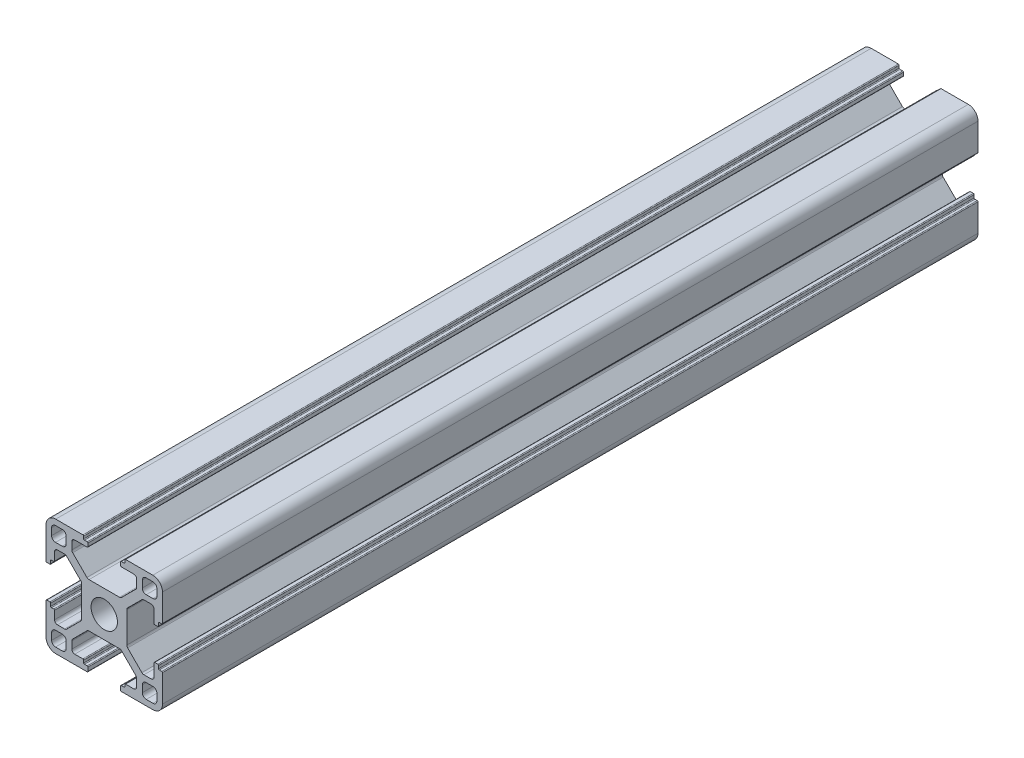
SolidWorks part; units mm, degrees
material "6063-T5"
ref_plane "Front Plane" through (0, 0, 0) normal (0, 0, 1) x (1, 0, 0)
ref_plane "Top Plane" through (0, 0, 0) normal (0, 1, 0) x (1, 0, 0)
ref_plane "Right Plane" through (0, 0, 0) normal (1, 0, 0) x (0, 0, -1)
sketch "Sketch1" plane through (0, 0, 0) normal (0, 0, 1) x (1, 0, 0)
  line L0 (0, 2.5) -> (0, 10.6)
  line L1 (2.5, 30) -> (9.5, 30)
  line L2 (30, 27.5) -> (30, 20.5)
  line L3 (27.5, 0) -> (19.4, 0)
  line L4 (19.464, 9.1128) -> (23.1303, 5.4465)
  line L5 (21.0197, 10.536) -> (24.686, 6.8697)
  line L6 (10.536, 21.0197) -> (6.8697, 24.686)
  line L7 (8.9803, 19.464) -> (5.314, 23.1303)
  line L8 (11.0663, 20.8) -> (18.9337, 20.8)
  line L9 (20.8, 18.9337) -> (20.8, 11.0663)
  line L10 (18.9337, 9.3324) -> (11.0663, 9.3324)
  line L11 (9.2, 11.0663) -> (9.2, 18.9337)
  line L12 (0, 19.4) -> (0, 27.5)
  line L13 (30, 9.5) -> (30, 2.5)
  line L14 (19.4, 27.8) -> (22.6, 27.8)
  line L15 (10.6, 27.8) -> (7.4, 27.8)
  line L16 (10.6, 0) -> (2.5, 0)
  line L17 (2.2, 20.5) -> (2.2, 22.6)
  line L18 (2.2, 9.5) -> (2.2, 7.4)
  line L19 (9.5, 2.3324) -> (7.4, 2.3324)
  line L20 (19.464, 21.0197) -> (23.1303, 24.686)
  line L21 (21.0197, 19.464) -> (24.686, 23.1303)
  line L22 (8.9803, 10.536) -> (5.314, 6.8697)
  line L23 (10.536, 9.1128) -> (6.8697, 5.4465)
  line L24 (10.8, 28.8) -> (10.8, 28)
  line L25 (19.2, 28.8) -> (19.2, 28)
  line L26 (0.2, 19.2) -> (1, 19.2)
  line L27 (0.2, 10.8) -> (1, 10.8)
  line L28 (28.8, 19.2) -> (28, 19.2)
  line L29 (28.8, 10.8) -> (28, 10.8)
  line L30 (10.8, 0.2) -> (10.8, 1.1324)
  line L31 (19.2, 0.2) -> (19.2, 1.1324)
  line L32 (20.5, 30) -> (27.5, 30)
  line L33 (27.8, 19.4) -> (27.8, 22.6)
  line L34 (27.8, 10.6) -> (27.8, 7.4)
  line L35 (20.5, 2.2) -> (22.6, 2.2)
  line L36 (6.65, 27.05) -> (6.65, 25.2163)
  line L37 (23.35, 27.05) -> (23.35, 25.2163)
  line L38 (2.95, 23.35) -> (4.7837, 23.35)
  line L39 (27.05, 23.35) -> (25.2163, 23.35)
  line L40 (2.95, 6.65) -> (4.7837, 6.65)
  line L41 (6.65, 3.0824) -> (6.65, 4.9161)
  line L42 (23.35, 2.95) -> (23.35, 4.9161)
  line L43 (27.05, 6.65) -> (25.2163, 6.65)
  line L44 (29, 10.6) -> (29, 9.9)
  line L45 (29.8, 20.3) -> (29.2, 20.3)
  line L46 (29, 20.1) -> (29, 19.4)
  line L47 (29.2, 9.7) -> (29.8, 9.7)
  line L48 (19.4, 29) -> (20.1, 29)
  line L49 (9.7, 29.8) -> (9.7, 29.2)
  line L50 (9.9, 29) -> (10.6, 29)
  line L51 (20.3, 29.2) -> (20.3, 29.8)
  line L52 (9.7, 2.1324) -> (9.7, 1.5324)
  line L53 (9.9, 1.3324) -> (10.6, 1.3324)
  line L54 (19.4, 1.3324) -> (20.1, 1.3324)
  line L55 (20.3, 1.5324) -> (20.3, 2)
  line L56 (2, 20.3) -> (1.4, 20.3)
  line L57 (1.2, 20.1) -> (1.2, 19.4)
  line L58 (1.2, 10.6) -> (1.2, 9.9)
  line L59 (1.4, 9.7) -> (2, 9.7)
  line L60 (27.55, 1.45) -> (25.8, 1.45)
  line L61 (24.8, 2.45) -> (24.8, 4.2)
  line L62 (25.8, 5.2) -> (27.55, 5.2)
  line L63 (28.55, 4.2) -> (28.55, 2.45)
  line L64 (24.8, 25.8) -> (24.8, 27.55)
  line L65 (25.8, 28.55) -> (27.55, 28.55)
  line L66 (28.55, 27.55) -> (28.55, 25.8)
  line L67 (27.55, 24.8) -> (25.8, 24.8)
  line L68 (2.45, 28.55) -> (4.2, 28.55)
  line L69 (5.2, 27.55) -> (5.2, 25.8)
  line L70 (1.45, 2.45) -> (1.45, 4.2)
  line L71 (2.45, 5.2) -> (4.2, 5.2)
  line L72 (5.2, 4.2) -> (5.2, 2.45)
  line L73 (4.2, 1.45) -> (2.45, 1.45)
  line L74 (4.2, 24.8) -> (2.45, 24.8)
  line L75 (1.45, 25.8) -> (1.45, 27.55)
  circle A0 centre (15, 15) radius 3.4
  arc A1 (25.8, 1.45) -> (24.8, 2.45) centre (25.8, 2.45) cw
  arc A2 (27.55, 1.45) -> (28.55, 2.45) centre (27.55, 2.45) ccw
  arc A3 (27.55, 5.2) -> (28.55, 4.2) centre (27.55, 4.2) cw
  arc A4 (24.8, 4.2) -> (25.8, 5.2) centre (25.8, 4.2) cw
  arc A5 (1.45, 2.45) -> (2.45, 1.45) centre (2.45, 2.45) ccw
  arc A6 (5.2, 2.45) -> (4.2, 1.45) centre (4.2, 2.45) cw
  arc A7 (4.2, 5.2) -> (5.2, 4.2) centre (4.2, 4.2) cw
  arc A8 (1.45, 4.2) -> (2.45, 5.2) centre (2.45, 4.2) cw
  arc A9 (24.8, 25.8) -> (25.8, 24.8) centre (25.8, 25.8) ccw
  arc A10 (28.55, 25.8) -> (27.55, 24.8) centre (27.55, 25.8) cw
  arc A11 (27.55, 28.55) -> (28.55, 27.55) centre (27.55, 27.55) cw
  arc A12 (24.8, 27.55) -> (25.8, 28.55) centre (25.8, 27.55) cw
  arc A13 (4.2, 28.55) -> (5.2, 27.55) centre (4.2, 27.55) cw
  arc A14 (5.2, 25.8) -> (4.2, 24.8) centre (4.2, 25.8) cw
  arc A15 (2.45, 24.8) -> (1.45, 25.8) centre (2.45, 25.8) cw
  arc A16 (2.45, 28.55) -> (1.45, 27.55) centre (2.45, 27.55) ccw
  arc A17 (30, 2.5) -> (27.5, 0) centre (27.5, 2.5) cw
  arc A18 (0, 2.5) -> (2.5, 0) centre (2.5, 2.5) ccw
  arc A19 (27.5, 30) -> (30, 27.5) centre (27.5, 27.5) cw
  arc A20 (0, 27.5) -> (2.5, 30) centre (2.5, 27.5) cw
  arc A21 (0, 10.6) -> (0.2, 10.8) centre (0.2, 10.6) cw
  arc A22 (1.2, 10.6) -> (1, 10.8) centre (1, 10.6) ccw
  arc A23 (2, 9.7) -> (2.2, 9.5) centre (2, 9.5) cw
  arc A24 (9.7, 2.1324) -> (9.5, 2.3324) centre (9.5, 2.1324) ccw
  arc A25 (10.6, 1.3324) -> (10.8, 1.1324) centre (10.6, 1.1324) cw
  arc A26 (10.6, 0) -> (10.8, 0.2) centre (10.6, 0.2) ccw
  arc A27 (19.4, 0) -> (19.2, 0.2) centre (19.4, 0.2) cw
  arc A28 (19.4, 1.3324) -> (19.2, 1.1324) centre (19.4, 1.1324) ccw
  arc A29 (20.3, 2) -> (20.5, 2.2) centre (20.5, 2) cw
  arc A30 (28, 10.8) -> (27.8, 10.6) centre (28, 10.6) ccw
  arc A31 (29, 10.6) -> (28.8, 10.8) centre (28.8, 10.6) ccw
  arc A32 (29.8, 9.7) -> (30, 9.5) centre (29.8, 9.5) cw
  arc A33 (28, 19.2) -> (27.8, 19.4) centre (28, 19.4) cw
  arc A34 (29, 19.4) -> (28.8, 19.2) centre (28.8, 19.4) cw
  arc A35 (30, 20.5) -> (29.8, 20.3) centre (29.8, 20.5) cw
  arc A36 (20.3, 29.8) -> (20.5, 30) centre (20.5, 29.8) cw
  arc A37 (19.4, 29) -> (19.2, 28.8) centre (19.4, 28.8) ccw
  arc A38 (19.2, 28) -> (19.4, 27.8) centre (19.4, 28) ccw
  arc A39 (10.8, 28) -> (10.6, 27.8) centre (10.6, 28) cw
  arc A40 (0, 19.4) -> (0.2, 19.2) centre (0.2, 19.4) ccw
  arc A41 (1.2, 19.4) -> (1, 19.2) centre (1, 19.4) cw
  arc A42 (2, 20.3) -> (2.2, 20.5) centre (2, 20.5) ccw
  arc A43 (10.6, 29) -> (10.8, 28.8) centre (10.6, 28.8) cw
  arc A44 (9.5, 30) -> (9.7, 29.8) centre (9.5, 29.8) cw
  arc A45 (1.4, 20.3) -> (1.2, 20.1) centre (1.4, 20.1) ccw
  arc A46 (20.1, 29) -> (20.3, 29.2) centre (20.1, 29.2) ccw
  arc A47 (9.7, 29.2) -> (9.9, 29) centre (9.9, 29.2) ccw
  arc A48 (29.2, 20.3) -> (29, 20.1) centre (29.2, 20.1) ccw
  arc A49 (29, 9.9) -> (29.2, 9.7) centre (29.2, 9.9) ccw
  arc A50 (20.1, 1.3324) -> (20.3, 1.5324) centre (20.1, 1.5324) ccw
  arc A51 (1.2, 9.9) -> (1.4, 9.7) centre (1.4, 9.9) ccw
  arc A52 (9.7, 1.5324) -> (9.9, 1.3324) centre (9.9, 1.5324) ccw
  arc A53 (23.35, 25.2163) -> (23.1303, 24.686) centre (22.6, 25.2163) cw
  arc A54 (25.2163, 23.35) -> (24.686, 23.1303) centre (25.2163, 22.6) ccw
  arc A55 (20.8, 18.9337) -> (21.0197, 19.464) centre (21.55, 18.9337) cw
  arc A56 (18.9337, 20.8) -> (19.464, 21.0197) centre (18.9337, 21.55) ccw
  arc A57 (6.65, 25.2163) -> (6.8697, 24.686) centre (7.4, 25.2163) ccw
  arc A58 (11.0663, 20.8) -> (10.536, 21.0197) centre (11.0663, 21.55) cw
  arc A59 (4.7837, 23.35) -> (5.314, 23.1303) centre (4.7837, 22.6) cw
  arc A60 (9.2, 18.9337) -> (8.9803, 19.464) centre (8.45, 18.9337) ccw
  arc A61 (4.7837, 6.65) -> (5.314, 6.8697) centre (4.7837, 7.4) ccw
  arc A62 (9.2, 11.0663) -> (8.9803, 10.536) centre (8.45, 11.0663) cw
  arc A63 (6.65, 4.9161) -> (6.8697, 5.4465) centre (7.4, 4.9161) cw
  arc A64 (11.0663, 9.3324) -> (10.536, 9.1128) centre (11.0663, 8.5824) ccw
  arc A65 (18.9337, 9.3324) -> (19.464, 9.1128) centre (18.9337, 8.5824) cw
  arc A66 (20.8, 11.0663) -> (21.0197, 10.536) centre (21.55, 11.0663) ccw
  arc A67 (25.2163, 6.65) -> (24.686, 6.8697) centre (25.2163, 7.4) cw
  arc A68 (23.35, 4.9161) -> (23.1303, 5.4465) centre (22.6, 4.9161) ccw
  arc A69 (7.4, 2.3324) -> (6.65, 3.0824) centre (7.4, 3.0824) cw
  arc A70 (22.6, 2.2) -> (23.35, 2.95) centre (22.6, 2.95) ccw
  arc A71 (27.8, 7.4) -> (27.05, 6.65) centre (27.05, 7.4) cw
  arc A72 (27.8, 22.6) -> (27.05, 23.35) centre (27.05, 22.6) ccw
  arc A73 (22.6, 27.8) -> (23.35, 27.05) centre (22.6, 27.05) cw
  arc A74 (2.2, 7.4) -> (2.95, 6.65) centre (2.95, 7.4) ccw
  arc A75 (2.2, 22.6) -> (2.95, 23.35) centre (2.95, 22.6) cw
  arc A76 (7.4, 27.8) -> (6.65, 27.05) centre (7.4, 27.05) ccw
  point P115 (0, 0)
extrude "Boss-Extrude1" add sketch "Sketch1" along normal blind 210
